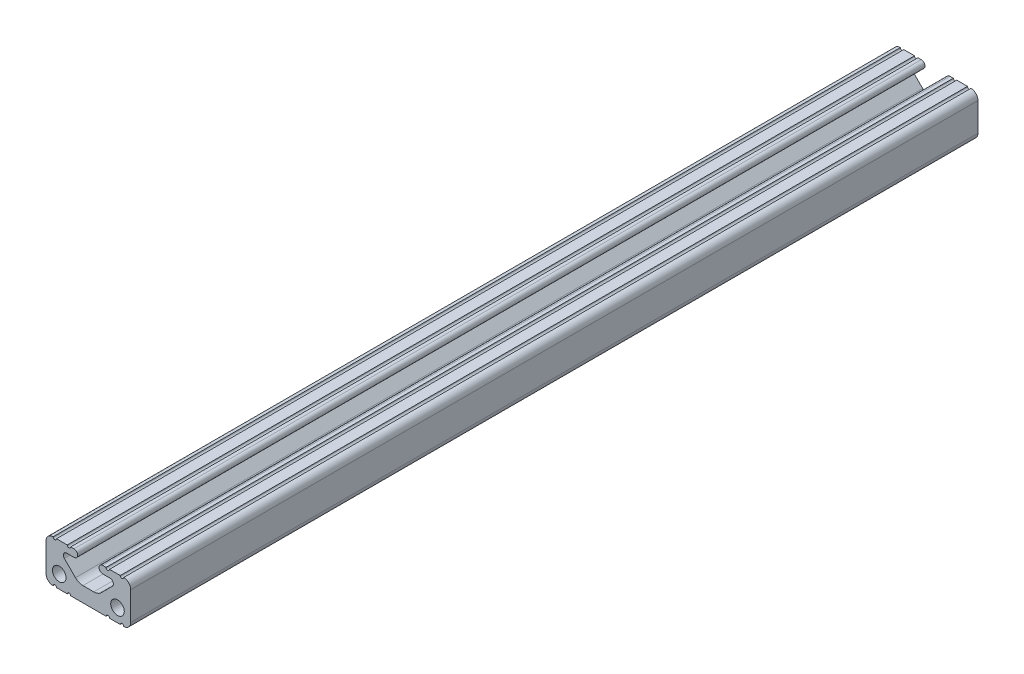
SolidWorks part; units mm, degrees
ref_plane "Front" through (0, 0, 0) normal (0, 0, 1) x (1, 0, 0)
ref_plane "Top" through (0, 0, 0) normal (0, 1, 0) x (1, 0, 0)
ref_plane "Right" through (0, 0, 0) normal (1, 0, 0) x (0, 0, -1)
sketch "Sketch1" plane through (0, 0, 0) normal (0, 0, 1) x (1, 0, 0)
  line L0 (-3.1974, 11.5951) -> (3.1974, 11.5951) construction
  line L1 (-7.504, 9.4742) -> (7.504, 9.4742) construction
  line L28 (-12.7, 10.5918) -> (-12.7, 2.1082)
  line L29 (-9.5504, 0) -> (-6.3246, 0)
  line L30 (-5.3086, 0) -> (5.3086, 0)
  line L31 (6.3246, 0) -> (9.5504, 0)
  line L32 (12.7, 2.1082) -> (12.7, 10.5918)
  line L33 (9.5504, 12.7) -> (6.3246, 12.7)
  line L34 (5.3086, 12.7) -> (4.3023, 12.7)
  line L35 (4.3023, 10.4902) -> (6.488, 10.4902)
  line L36 (7.2064, 8.7558) -> (3.8763, 5.4257)
  line L37 (1.6313, 4.4958) -> (-1.6313, 4.4958)
  line L38 (-3.8763, 5.4257) -> (-7.2064, 8.7558)
  line L39 (-6.488, 10.4902) -> (-4.3023, 10.4902)
  line L40 (-4.3023, 12.7) -> (-5.3086, 12.7)
  line L41 (-6.3246, 12.7) -> (-9.5504, 12.7)
  circle A0 centre (-8.7312, 3.9624) radius 2.032
  circle A1 centre (8.7312, 3.9624) radius 2.032
  arc A36 (-12.7, 2.1082) -> (-10.5791, 0) centre (-10.5918, 2.1082) ccw
  arc A37 (-9.5504, 0) -> (-10.5791, 0) centre (-10.0648, -0.0064) ccw
  arc A38 (-5.3086, 0) -> (-6.3246, 0) centre (-5.8166, 0) ccw
  arc A39 (6.3246, 0) -> (5.3086, 0) centre (5.8166, 0) ccw
  arc A40 (10.5791, 0) -> (9.5504, 0) centre (10.0648, -0.0064) ccw
  arc A41 (10.5791, 0) -> (12.7, 2.1082) centre (10.5918, 2.1082) ccw
  arc A42 (12.7, 10.5918) -> (10.5791, 12.7) centre (10.5918, 10.5918) ccw
  arc A43 (9.5504, 12.7) -> (10.5791, 12.7) centre (10.0648, 12.7063) ccw
  arc A44 (5.3086, 12.7) -> (6.3246, 12.7) centre (5.8166, 12.7) ccw
  arc A45 (4.3023, 12.7) -> (4.3023, 10.4902) centre (4.3023, 11.5951) ccw
  arc A46 (7.2064, 8.7558) -> (6.488, 10.4902) centre (6.488, 9.4742) ccw
  arc A47 (1.6313, 4.4958) -> (3.8763, 5.4257) centre (1.6313, 7.6708) ccw
  arc A48 (-3.8763, 5.4257) -> (-1.6313, 4.4958) centre (-1.6313, 7.6708) ccw
  arc A49 (-6.488, 10.4902) -> (-7.2064, 8.7558) centre (-6.488, 9.4742) ccw
  arc A50 (-4.3023, 10.4902) -> (-4.3023, 12.7) centre (-4.3023, 11.5951) ccw
  arc A51 (-6.3246, 12.7) -> (-5.3086, 12.7) centre (-5.8166, 12.7) ccw
  arc A52 (-10.5791, 12.7) -> (-9.5504, 12.7) centre (-10.0648, 12.7063) ccw
  arc A53 (-10.5791, 12.7) -> (-12.7, 10.5918) centre (-10.5918, 10.5918) ccw
extrude "Boss-Extrude1" add sketch "Sketch1" along normal mid plane 254
